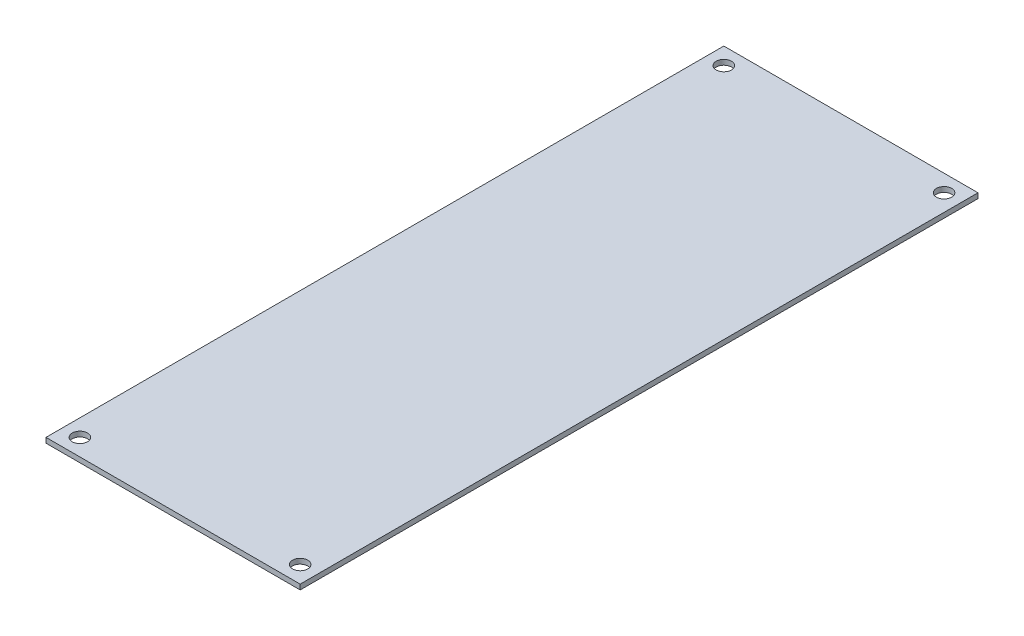
SolidWorks part; units mm, degrees
ref_plane "Front Plane" through (0, 0, 0) normal (0, 0, 1) x (1, 0, 0)
ref_plane "Top Plane" through (0, 0, 0) normal (0, 1, 0) x (1, 0, 0)
ref_plane "Right Plane" through (0, 0, 0) normal (1, 0, 0) x (0, 0, -1)
sketch "Sketch1" plane through (0, 0, 0) normal (0, 1, 0) x (1, 0, 0)
  line L0 (0, 0) -> (75, 0)
  line L1 (75, 0) -> (75, 200)
  line L2 (75, 200) -> (0, 200)
  line L3 (0, 200) -> (0, 0)
  dimension "D1" = 200
  dimension "D2" = 75
extrude "Boss-Extrude1" add sketch "Sketch1" along normal mid plane 1.5
sketch "Sketch2" plane through (0, 0.75, 0) normal (0, 1, 0) x (1, 0, 0)
  line L0 (75, 200) -> (0, 200) construction
  line L1 (75, 0) -> (75, 200) construction
  line L4 (0, 0) -> (75, 0) construction
  line L5 (0, 200) -> (0, 0) construction
  circle A0 centre (5, 195) radius 2.25
  circle A1 centre (70, 195) radius 2.25
  circle A2 centre (5, 5) radius 2.25
  circle A3 centre (70, 5) radius 2.25
  point P8 (0, 0)
  point P9 (0, 0)
  point P10 (0, 0)
  point P11 (0, 0)
  dimension "D1" = 4.5
  dimension "D2" = 5
  dimension "D3" = 5
  dimension "D4" = 5
  dimension "D5" = 5
extrude "Cut-Extrude1" cut sketch "Sketch2" against normal through all both and the other way through all
